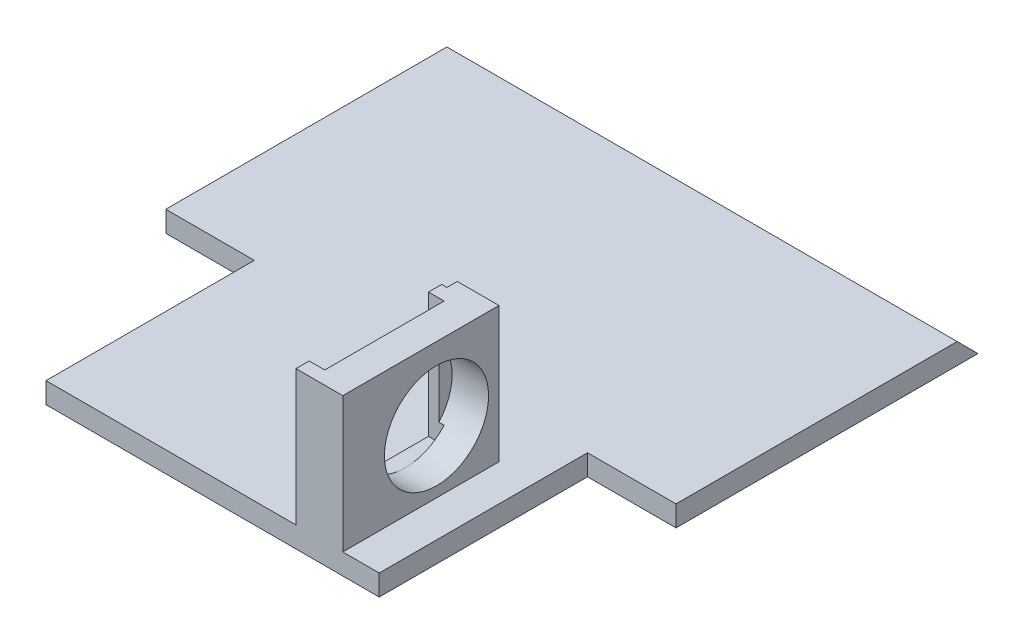
SolidWorks part; units mm, degrees
material "1023 Листовая углеродистая сталь (SS)"
ref_plane "Спереди" through (0, 0, 0) normal (0, 0, 1) x (1, 0, 0)
ref_plane "Сверху" through (0, 0, 0) normal (0, 1, 0) x (1, 0, 0)
ref_plane "Справа" through (0, 0, 0) normal (1, 0, 0) x (0, 0, -1)
sketch "Эскиз1" plane through (0, 0, 0) normal (0, 1, 0) x (1, 0, 0)
  line L0 (0, 24.5) -> (0, -24.5) construction
  line L1 (-25, -25) -> (25, -25) construction
  line L2 (-25, -25) -> (-25, 25) construction
  line L3 (-25, 25) -> (25, 25) construction
  line L4 (25, -25) -> (25, 25) construction
  line L5 (-25, -25) -> (25, 25) construction
  line L6 (-25, 25) -> (25, -25) construction
  line L7 (16, -24.5) -> (-16, -24.5)
  line L8 (24.5, -4.5) -> (24.5, 24.5)
  line L9 (24.5, 24.5) -> (-24.5, 24.5)
  line L10 (-24.5, -4.5) -> (-24.5, 24.5)
  line L11 (24.5, -24.5) -> (-24.5, 24.5) construction
  line L12 (24.5, 24.5) -> (-24.5, -24.5) construction
  line L13 (16, -4.5) -> (24.5, -4.5)
  line L14 (-24.5, -4.5) -> (-16, -4.5)
  line L15 (-16, -4.5) -> (-16, -24.5)
  line L16 (-16, -24.5) -> (16, -24.5)
  line L17 (16, -4.5) -> (16, -24.5)
  line L18 (-16, -4.5) -> (16, -24.5) construction
  line L19 (-16, -24.5) -> (16, -4.5) construction
  point P0 (0, 0)
  point P6 (0, 0)
  point P13 (0, -14.5)
  dimension "D1" = 50
  dimension "D2" = 50
  dimension "D3" = 49
  dimension "D4" = 8.5
  dimension "D6" = 20
extrude "Бобышка-Вытянуть1" add sketch "Эскиз1" along normal blind 2 contours L17 L13 L8 L9 L10 L14 L15 L7
sketch "Эскиз2" plane through (16, 0, 0) normal (1, 0, 0) x (0, 0, -1)
  line L0 (-10, 13) -> (-10, 3) construction
  line L5 (-24.5, 2) -> (-10.5, 2)
  line L6 (-24.5, 2) -> (-24.5, 15)
  line L7 (-24.5, 15) -> (-10.5, 15)
  line L8 (-10.5, 2) -> (-10.5, 15)
  line L9 (-19.5, 14) -> (-11.5, 14) construction
  circle A0 centre (-15.5, 8) radius 1.5
  dimension "D1" = 3
  dimension "D2" = 0.5
  dimension "D3" = 1
extrude "Бобышка-Вытянуть2" add sketch "Эскиз2" against normal blind 4.5 from offset 2 offset against normal yes
sketch "Эскиз3" plane through (0, 15, 0) normal (0, 1, 0) x (1, 0, 0)
  line L0 (9.5, -17.5) -> (13.515, -17.5) construction
  line L1 (9.5, -10.5) -> (8, -10.5)
  line L2 (9.5, -10.5) -> (9.5, -11.7682)
  line L3 (9.5, -11.7682) -> (8, -11.7682)
  line L4 (8, -10.5) -> (8, -11.7682)
  line L5 (9.5, -10.5) -> (9.5, -24.5) construction
  line L6 (9.5, -23.2318) -> (8, -23.2318)
  line L7 (8, -24.5) -> (8, -23.2318)
  line L8 (9.5, -24.5) -> (8, -24.5)
  line L9 (9.5, -24.5) -> (9.5, -23.2318)
  line L10 (7.5, -20.5) -> (7.5, -10.5) construction
  dimension "D1" = 0.5
extrude "Бобышка-Вытянуть3" add sketch "Эскиз3" against normal up to surface (13 mm away) up to face at (3.9167, 2, 7.3333)
sketch "Эскиз4" plane through (0, 0, 11.7682) normal (0, 0, 1) x (1, 0, 0)
  line L0 (9.5, 2) -> (9.5, 15) construction
  line L1 (8, 2) -> (9.5, 2)
  line L2 (8, 2) -> (8, 3)
  line L3 (8, 3) -> (9.5, 3)
  line L4 (9.5, 2) -> (9.5, 3)
  dimension "D1" = 1
extrude "Бобышка-Вытянуть4" add sketch "Эскиз4" along normal up to surface (11.4636 mm away) up to face at (8.75, 8.5, 23.2318)
sketch "Эскиз5" plane through (0, 15, 0) normal (0, 1, 0) x (1, 0, 0)
  line L0 (8, -24.5) -> (14, -24.5) construction
  line L1 (14, -10.5) -> (12.5, -10.5)
  line L2 (14, -10.5) -> (14, -24.5)
  line L3 (14, -24.5) -> (12.5, -24.5)
  line L4 (12.5, -10.5) -> (12.5, -24.5)
  dimension "D1" = 1.5
extrude "Вырез-Вытянуть1" cut sketch "Эскиз5" against normal up to surface (13 mm away) up to face at (3.6667, 2, 7.3333)
sketch "Эскиз7" plane through (0, 15, 0) normal (0, 1, 0) x (1, 0, 0)
  line L6 (12.5, -10.5) -> (8.5, -10.5)
  line L7 (12.5, -10.5) -> (12.5, -9.5)
  line L8 (12.5, -9.5) -> (8.5, -9.5)
  line L9 (8.5, -10.5) -> (8.5, -9.5)
  dimension "D1" = 4
  dimension "D2" = 1
extrude "Бобышка-Вытянуть5" add sketch "Эскиз7" against normal up to surface (13 mm away) up to face at (3.4167, 2, 7.3333)
sketch "Эскиз6" plane through (12.5, 0, 0) normal (1, 0, 0) x (0, 0, -1)
  circle A0 centre (-15.5, 8) radius 5
  dimension "D1" = 10
extrude "Вырез-Вытянуть2" cut sketch "Эскиз6" against normal blind 4 from offset 0.5
sketch "Эскиз8" plane through (24.5, 0, 0) normal (1, 0, 0) x (0, 0, -1)
  line L0 (24.5, 0) -> (22.5, 2)
  line L1 (-4.5, 2) -> (24.5, 2) construction
  line L2 (-4.5, 0) -> (24.5, 0) construction
  line L3 (22.5, 2) -> (24.5, 2)
  line L4 (24.5, 2) -> (24.5, 0)
  dimension "D1" = 45
extrude "Вырез-Вытянуть3" cut sketch "Эскиз8" against normal up to surface (49 mm away) up to face at (-24.5, 1, -10)
